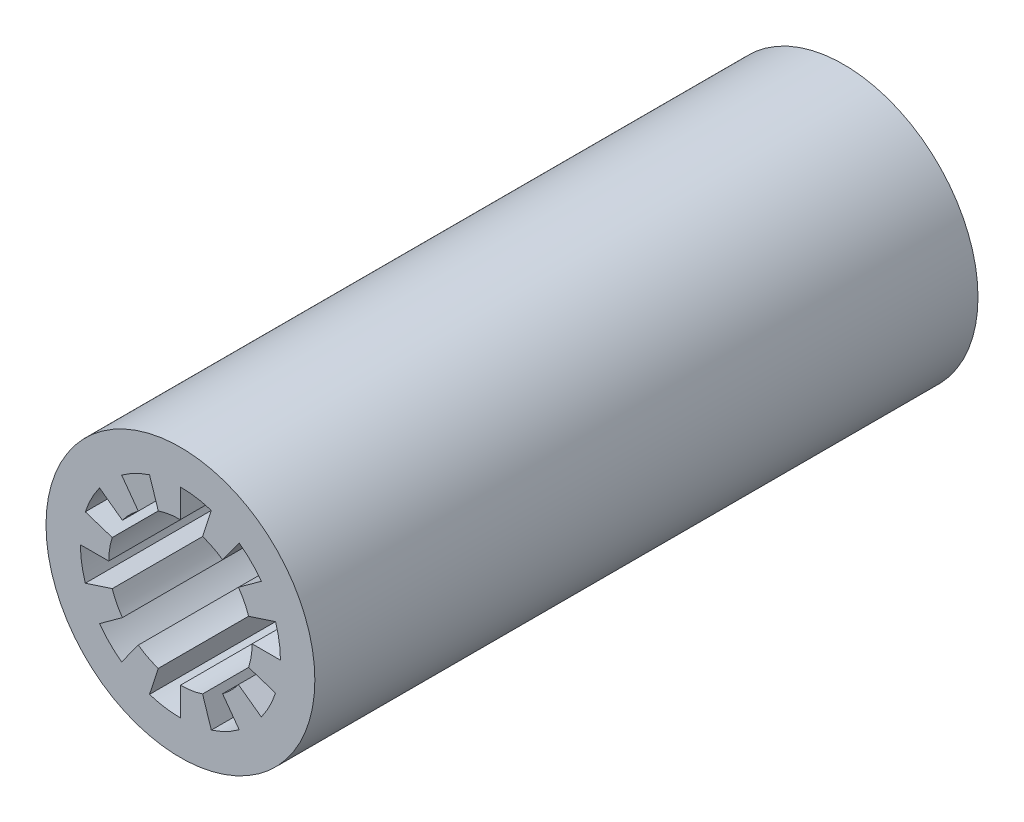
SolidWorks part; units mm, degrees
ref_plane "Front" through (0, 0, 0) normal (0, 0, 1) x (1, 0, 0)
ref_plane "Top" through (0, 0, 0) normal (0, 1, 0) x (1, 0, 0)
ref_plane "Right" through (0, 0, 0) normal (1, 0, 0) x (0, 0, -1)
sketch "Эскиз1" plane through (0, 0, 0) normal (0, 0, 1) x (1, 0, 0)
  line B0 (0, 5.58) -> (0, 4)
  line B1 (1.7243, 5.3069) -> (1.2361, 3.8042)
  line B2 (3.2798, 4.5143) -> (2.3511, 3.2361)
  line B3 (4.5143, 3.2798) -> (3.2361, 2.3511)
  line B4 (5.3069, 1.7243) -> (3.8042, 1.2361)
  line B5 (5.58, 0) -> (4, 0)
  line B6 (5.3069, -1.7243) -> (3.8042, -1.2361)
  line B7 (4.5143, -3.2798) -> (3.2361, -2.3511)
  line B8 (3.2798, -4.5143) -> (2.3511, -3.2361)
  line B9 (1.7243, -5.3069) -> (1.2361, -3.8042)
  line B10 (0, -5.58) -> (0, -4)
  line B11 (-1.7243, -5.3069) -> (-1.2361, -3.8042)
  line B12 (-3.2798, -4.5143) -> (-2.3511, -3.2361)
  line B13 (-4.5143, -3.2798) -> (-3.2361, -2.3511)
  line B14 (-5.3069, -1.7243) -> (-3.8042, -1.2361)
  line B15 (-5.58, 0) -> (-4, 0)
  line B16 (-5.3069, 1.7243) -> (-3.8042, 1.2361)
  line B17 (-4.5143, 3.2798) -> (-3.2361, 2.3511)
  line B18 (-3.2798, 4.5143) -> (-2.3511, 3.2361)
  line B19 (-1.7243, 5.3069) -> (-1.2361, 3.8042)
  arc B20 (0, 4) -> (-1.2361, 3.8042) centre (0, 0) ccw
  arc B21 (-4.5143, 3.2798) -> (-5.3069, 1.7243) centre (0, 0) ccw
  circle B22 centre (0, 0) radius 7.5
  arc B23 (2.3511, 3.2361) -> (1.2361, 3.8042) centre (0, 0) ccw
  arc B24 (3.8042, 1.2361) -> (3.2361, 2.3511) centre (0, 0) ccw
  arc B25 (3.8042, -1.2361) -> (4, 0) centre (0, 0) ccw
  arc B26 (2.3511, -3.2361) -> (3.2361, -2.3511) centre (0, 0) ccw
  arc B27 (0, -4) -> (1.2361, -3.8042) centre (0, 0) ccw
  arc B28 (-2.3511, -3.2361) -> (-1.2361, -3.8042) centre (0, 0) ccw
  arc B29 (-3.8042, -1.2361) -> (-3.2361, -2.3511) centre (0, 0) ccw
  arc B30 (-3.8042, 1.2361) -> (-4, 0) centre (0, 0) ccw
  arc B31 (-2.3511, 3.2361) -> (-3.2361, 2.3511) centre (0, 0) ccw
  arc B32 (-1.7243, 5.3069) -> (-3.2798, 4.5143) centre (0, 0) ccw
  arc B33 (1.7243, 5.3069) -> (0, 5.58) centre (0, 0) ccw
  arc B34 (4.5143, 3.2798) -> (3.2798, 4.5143) centre (0, 0) ccw
  arc B35 (5.58, 0) -> (5.3069, 1.7243) centre (0, 0) ccw
  arc B36 (4.5143, -3.2798) -> (5.3069, -1.7243) centre (0, 0) ccw
  arc B37 (1.7243, -5.3069) -> (3.2798, -4.5143) centre (0, 0) ccw
  arc B38 (-1.7243, -5.3069) -> (0, -5.58) centre (0, 0) ccw
  arc B39 (-4.5143, -3.2798) -> (-3.2798, -4.5143) centre (0, 0) ccw
  arc B40 (-5.58, 0) -> (-5.3069, -1.7243) centre (0, 0) ccw
sketch_block_instance "Блок1-1"
sketch_block "Блок1" parameters "D1"=5.6
extrude "Бобышка-Вытянуть1" add sketch "Эскиз1" along normal blind 37
